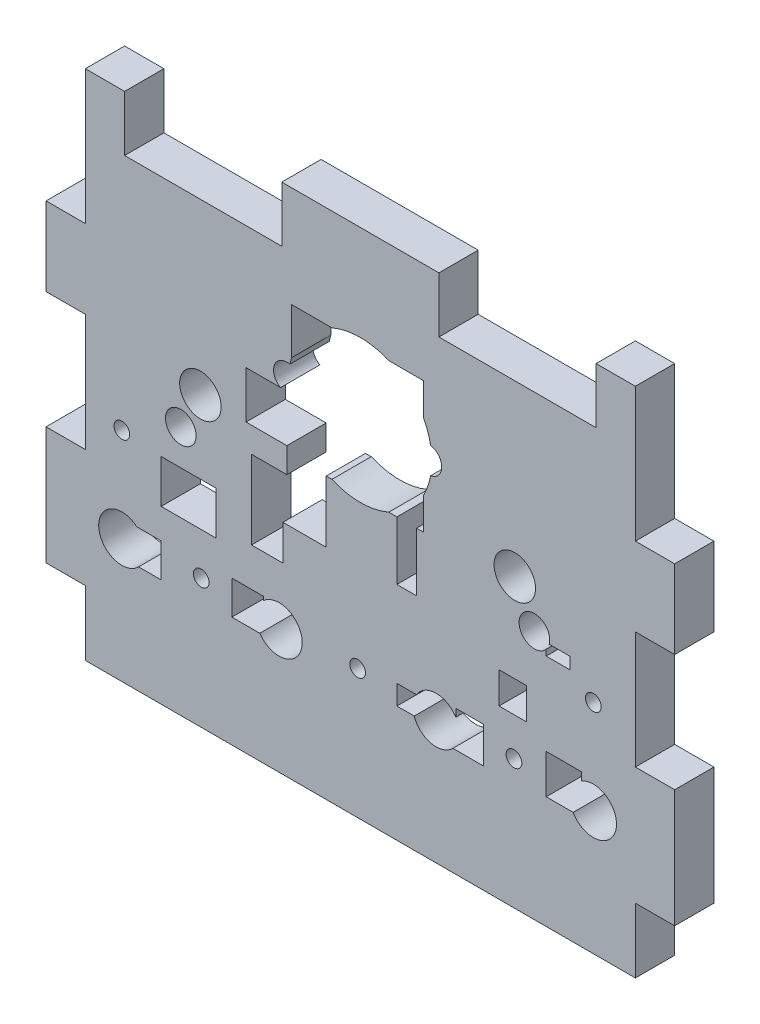
SolidWorks part; units mm, degrees
material "Balsa"
ref_plane "Plan de face" through (0, 0, 0) normal (0, 0, 1) x (1, 0, 0)
ref_plane "Plan de dessus" through (0, 0, 0) normal (0, 1, 0) x (1, 0, 0)
ref_plane "Plan de droite" through (0, 0, 0) normal (1, 0, 0) x (0, 0, -1)
sketch "Esquisse1" plane through (0, 0, 0) normal (0, 0, 1) x (1, 0, 0)
  line L0 (26.2493, 52.35) -> (43.0493, 52.35)
  line L1 (0, 58.15) -> (70, 58.15)
  line L2 (0, 58.15) -> (0, 0)
  line L3 (0, 0) -> (70, 0)
  line L4 (70, 58.15) -> (70, 0)
  line L5 (43.0493, 52.35) -> (43.0493, 45.7)
  line L6 (43.0493, 45.7) -> (43.6493, 45.7)
  line L7 (21.1493, 33.3) -> (25.6493, 33.3)
  line L8 (42.1493, 28.2) -> (39.6493, 28.2)
  line L10 (39.6493, 28.2) -> (39.6493, 35.65)
  line L11 (30.6493, 35.65) -> (39.6493, 35.65)
  line L12 (30.6493, 35.65) -> (30.6493, 27.8)
  line L13 (25.1493, 23.3) -> (25.1493, 27.8)
  line L14 (25.1493, 23.3) -> (21.1493, 23.3)
  line L16 (21.1493, 23.3) -> (21.1493, 33.3)
  line L17 (43.6493, 42.3) -> (43.0493, 42.3)
  line L18 (20.4493, 36.5) -> (20.4493, 42.5)
  line L19 (26.2493, 52.35) -> (26.2493, 45.7)
  line L20 (43.0493, 42.3) -> (43.0493, 35.65)
  line L21 (25.6493, 33.3) -> (25.6493, 36.5)
  line L23 (25.6493, 36.5) -> (20.4493, 36.5)
  line L24 (42.1493, 35.65) -> (42.1493, 28.2)
  line L25 (9.6493, 27.3) -> (16.6493, 27.3)
  line L26 (16.6493, 27.3) -> (16.6493, 21.8)
  line L27 (16.6493, 21.8) -> (9.6493, 21.8)
  line L28 (9.6493, 21.8) -> (9.6493, 27.3)
  line L29 (6.5572, 18) -> (9.6493, 18)
  line L31 (9.6493, 18) -> (9.6493, 13.7)
  line L32 (9.6493, 13.7) -> (6.7706, 13.7)
  line L34 (26.2493, 45.7) -> (25.6493, 45.7)
  line L36 (22.6493, 17.9185) -> (22.6493, 18.4)
  line L37 (22.6493, 18.4) -> (18.6493, 18.4)
  line L38 (18.6493, 18.4) -> (18.6493, 14.1)
  line L39 (18.6493, 14.1) -> (22.2039, 14.1)
  line L43 (42.1393, 17.3) -> (39.6493, 17.3)
  line L44 (39.6493, 17.3) -> (39.6493, 14.8)
  line L45 (39.6493, 14.8) -> (41.8564, 14.8)
  line L47 (25.1493, 27.8) -> (30.6493, 27.8)
  line L49 (47.1493, 17.316) -> (47.1493, 18.3)
  line L50 (47.1493, 18.3) -> (50.6493, 18.3)
  line L53 (50.6493, 18.3) -> (50.6493, 13.7)
  line L54 (50.6493, 13.7) -> (46.7706, 13.7)
  line L55 (42.1493, 35.65) -> (43.0493, 35.65)
  line L56 (52.6493, 25.3) -> (56.1493, 25.3)
  line L58 (56.1493, 25.3) -> (56.1493, 21.3)
  line L60 (56.1493, 21.3) -> (52.6493, 21.3)
  line L61 (52.6493, 21.3) -> (52.6493, 25.3)
  line L62 (58.6493, 30.554) -> (58.6493, 29.8)
  line L64 (58.6493, 29.8) -> (61.6493, 29.8)
  line L65 (61.6493, 29.8) -> (61.6493, 31.3)
  line L66 (61.6493, 31.3) -> (59.0341, 31.3)
  line L67 (20.4493, 42.5) -> (24.8493, 42.5)
  line L68 (63.1493, 19.3) -> (63.1493, 18.2902)
  line L70 (58.6493, 14.3) -> (58.6493, 19.3)
  line L71 (58.6493, 19.3) -> (63.1493, 19.3)
  line L72 (58.6493, 14.3) -> (62.0802, 14.3)
  arc A0 (43.6493, 45.7) -> (43.6493, 42.3) centre (43.6493, 44) cw
  arc A1 (25.6493, 45.7) -> (24.8493, 42.5) centre (25.6493, 44) ccw
  circle A3 centre (12.1493, 31.8) radius 1.95
  arc A4 (58.6493, 30.554) -> (59.0341, 31.3) centre (57.1493, 31.8) cw
  arc A5 (42.1393, 17.3) -> (47.1493, 17.316) centre (44.6493, 15.75) cw
  arc A6 (63.1493, 18.2902) -> (62.0802, 14.3) centre (64.6493, 15.75) cw
  arc A7 (22.2039, 14.1) -> (22.6493, 17.9185) centre (24.6493, 15.75) ccw
  arc A8 (6.5572, 18) -> (6.7706, 13.7) centre (4.6493, 15.75) ccw
  circle A9 centre (4.6493, 27.7) radius 1
  circle A10 centre (14.7493, 16.45) radius 1
  circle A11 centre (34.6493, 16.45) radius 1
  circle A12 centre (54.5493, 16.45) radius 1
  circle A13 centre (64.6493, 27.7) radius 1
  circle A14 centre (54.6545, 36.5743) radius 2.6401
  circle A15 centre (14.6441, 36.5743) radius 2.6401
  arc A16 (41.8564, 14.8) -> (46.7706, 13.7) centre (44.6493, 15.75) ccw
  dimension "D1" = 70
  dimension "D2" = 58.15
extrude "Boss.-Extru.1" add sketch "Esquisse1" along normal blind 5
sketch "Esquisse2" plane through (0, 0, 5) normal (0, 0, 1) x (1, 0, 0)
  line L0 (0, 0) -> (70, 0) construction
  line L1 (65, 0) -> (55, 0) construction
  line L2 (65, 0) -> (65, 1.46) construction
  line L3 (65, 1.46) -> (55, 1.46) construction
  line L4 (55, 0) -> (55, 1.46) construction
  line L5 (70, 0) -> (70, 58.15) construction
  line L6 (35, 0) -> (35, 58.15) construction
  line L7 (50, 1.46) -> (50, 0) construction
  line L8 (70, 58.15) -> (0, 58.15) construction
  line L9 (20, 1.46) -> (20, 0) construction
  line L10 (15, 0) -> (15, 1.46) construction
  line L11 (5, 1.46) -> (15, 1.46) construction
  line L12 (5, 0) -> (5, 1.46) construction
  line L13 (5, 0) -> (15, 0) construction
  line L14 (50, 0) -> (20, 0) construction
  line L15 (20, 1.46) -> (50, 1.46) construction
  circle A0 centre (35, 44) radius 9.1
  dimension "D1" = 1.46
  dimension "D2" = 5
  dimension "D3" = 10
  dimension "D4" = 5
extrude "Créneaux -" cut sketch "Esquisse2" against normal blind 5
sketch "Esquisse3" plane through (0, 0, 5) normal (0, 0, 1) x (1, 0, 0)
  line L1 (0, 0) -> (70, 0) construction
  line L5 (0, 58.15) -> (0, 0) construction
  line L11 (45, 58.15) -> (45, 65.22)
  line L15 (35, 58.15) -> (35, 1.46) construction
  line L16 (0, 58.15) -> (5, 58.15)
  line L17 (0, 58.15) -> (0, 65.22)
  line L18 (70, 58.15) -> (0, 58.15) construction
  line L28 (0, 65.22) -> (5, 65.22)
  line L29 (0, 8.25) -> (-5, 8.25)
  line L30 (0, 8.25) -> (0, 23.25)
  line L31 (0, 23.25) -> (-5, 23.25)
  line L32 (-5, 8.25) -> (-5, 23.25)
  line L33 (0, 48.15) -> (-5, 48.15)
  line L34 (0, 48.15) -> (0, 38.15)
  line L35 (0, 38.15) -> (-5, 38.15)
  line L36 (-5, 48.15) -> (-5, 38.15)
  line L37 (75, 48.15) -> (75, 38.15)
  line L38 (70, 38.15) -> (75, 38.15)
  line L39 (70, 48.15) -> (70, 38.15)
  line L40 (70, 48.15) -> (75, 48.15)
  line L41 (75, 8.25) -> (75, 23.25)
  line L42 (70, 23.25) -> (75, 23.25)
  line L43 (70, 8.25) -> (70, 23.25)
  line L44 (70, 8.25) -> (75, 8.25)
  line L45 (5, 58.15) -> (5, 65.22)
  line L46 (25, 58.15) -> (45, 58.15)
  line L47 (25, 58.15) -> (25, 65.22)
  line L48 (25, 65.22) -> (45, 65.22)
  line L49 (65, 58.15) -> (65, 65.22)
  line L50 (70, 65.22) -> (65, 65.22)
  line L51 (70, 58.15) -> (70, 65.22)
  line L52 (70, 58.15) -> (65, 58.15)
  dimension "D2" = 8.25
  dimension "D3" = 15
  dimension "D4" = 5
  dimension "D5" = 10
  dimension "D6" = 10
  dimension "D7" = 5
  dimension "D8" = 5
  dimension "D9" = 7.07
  dimension "D10" = 20
extrude "Créneaux +" add sketch "Esquisse3" against normal blind 5
